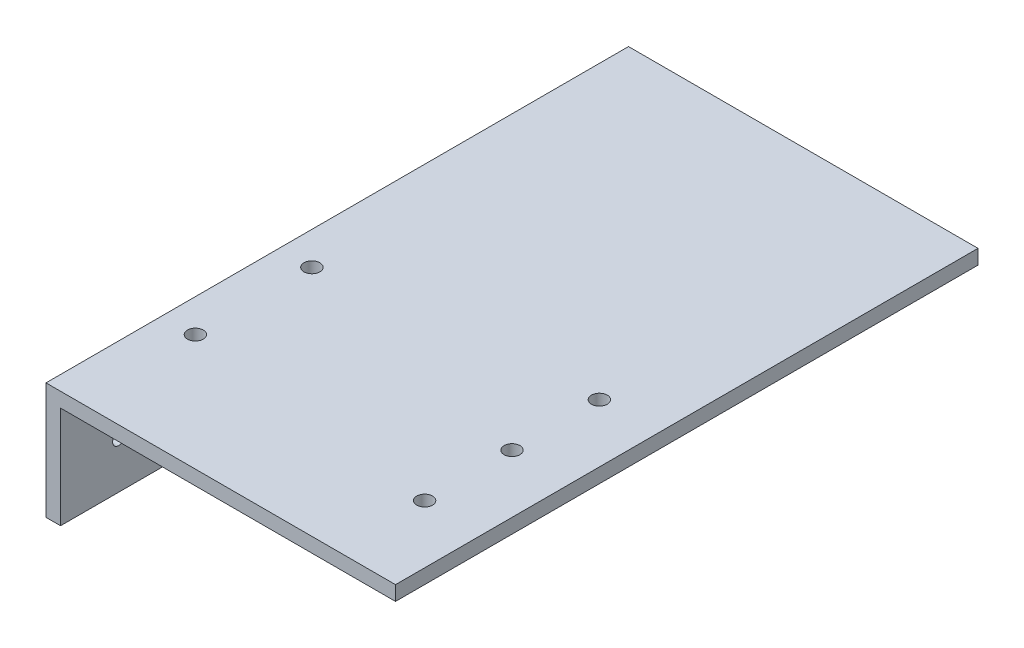
SolidWorks part; units mm, degrees
ref_plane "Front Plane" through (0, 0, 0) normal (0, 0, 1) x (1, 0, 0)
ref_plane "Top Plane" through (0, 0, 0) normal (0, 1, 0) x (1, 0, 0)
ref_plane "Right Plane" through (0, 0, 0) normal (1, 0, 0) x (0, 0, -1)
sketch "Sketch2" plane through (0, 0, 0) normal (0, 0, 1) x (1, 0, 0)
  line L0 (0, 0) -> (-76.2, 0)
  line L1 (-76.2, 0) -> (-76.2, -25.4)
  line L2 (-76.2, -25.4) -> (-73.025, -25.4)
  line L3 (-73.025, -25.4) -> (-73.025, -3.175)
  line L4 (-73.025, -3.175) -> (0, -3.175)
  line L5 (0, -3.175) -> (0, 0)
  dimension "D1" = 76.2
  dimension "D2" = 25.4
  dimension "D3" = 3.175
  dimension "D4" = 3.175
extrude "Boss-Extrude1" add sketch "Sketch2" along normal blind 76.2
sketch "Sketch7" plane through (-76.2, 0, 0) normal (-1, 0, 0) x (0, 0, 1)
  line L1 (0, 0) -> (0, -25.4) construction
  line L2 (0, -15.24) -> (38.1, -15.24) construction
  line L7 (36.449, -16.9885) -> (39.751, -13.4915) construction
  line L8 (36.449, -13.4915) -> (39.751, -16.9885) construction
  circle A0 centre (38.1, -15.24) radius 3.175
  dimension "D1" = 38.1
  dimension "D2" = 3.302
extrude "Cut-Extrude1" cut sketch "Sketch7" against normal up to next
hole_wizard "Tap Drill for #8-32 Tap2" positions "Sketch10" profile "Sketch9" hole size "#8-32" standard "ANSI Inch" end condition through all
sketch "Sketch10" plane through (0, 0, 0) normal (0, 1, 0) x (1, 0, 0)
  line L0 (0, 0) -> (-76.2, 0) construction
  line L1 (0, -76.2) -> (0, 0) construction
  point P0 (-12.7, -19.05)
  point P2 (-12.7, -38.1)
  point P4 (-12.7, -57.15)
  dimension "D1" = 19.05
  dimension "D2" = 19.05
  dimension "D3" = 19.05
  dimension "D4" = 12.7
sketch "Sketch9" plane through (-12.7, 0, 19.05) normal (1, 0, 0) x (0, 0, 1)
  line L0 (0, 0) -> (0, 25.4)
  line L1 (0, 25.4) -> (1.7272, 25.4)
  line L2 (1.7272, 25.4) -> (1.7272, 0)
  line L5 (1.7272, 0) -> (0, 0)
  line L11 (0, -6.35) -> (0, 107.95) construction
  dimension "Thru Hole Dia." = 3.4544
  dimension "Thru Hole Depth" = 25.4
hole_wizard "Tap Drill for #8-32 Tap4" positions "Sketch15" profile "Sketch14" hole size "#8-32" standard "ANSI Inch" end condition up to next
sketch "Sketch15" plane through (0, 0, 0) normal (0, 1, 0) x (1, 0, 0)
  line L0 (0, 0) -> (-76.2, 0) construction
  point P0 (-69.0285, -25.4)
  point P2 (-69.0285, -50.8)
  dimension "D1" = 25.4
  dimension "D2" = 25.4
sketch "Sketch14" plane through (-69.0285, 0, 25.4) normal (1, 0, 0) x (0, 0, 1)
  line L0 (0, 0) -> (0, 3.175)
  line L1 (0, 3.175) -> (1.7272, 3.175)
  line L2 (1.7272, 3.175) -> (1.7272, 0)
  line L5 (1.7272, 0) -> (0, 0)
  line L11 (0, -6.35) -> (0, 107.95) construction
  dimension "Thru Hole Dia." = 3.4544
  dimension "Thru Hole Depth" = 3.175
hole_wizard "Tap Drill for #6-32 Tap1" positions "Sketch17" profile "Sketch16" hole size "#6-32" standard "ANSI Inch" end condition up to next
sketch "Sketch17" plane through (-76.2, 0, 0) normal (-1, 0, 0) x (0, 0, 1)
  line L0 (76.2, 0) -> (0, 0) construction
  line L1 (76.2, 0) -> (76.2, -25.4) construction
  point P0 (50.8, -15.24)
  point P2 (63.5, -15.24)
  dimension "D1" = 12.7
  dimension "D2" = 15.24
  dimension "D3" = 12.7
sketch "Sketch16" plane through (-76.2, -15.24, 50.8) normal (0, 1, 0) x (0, 0, 1)
  line L0 (0, 0) -> (0, 3.175)
  line L1 (0, 3.175) -> (1.3525, 3.175)
  line L2 (1.3525, 3.175) -> (1.3525, 0)
  line L5 (1.3525, 0) -> (0, 0)
  line L11 (0, -6.35) -> (0, 107.95) construction
  dimension "Thru Hole Dia." = 2.7051
  dimension "Thru Hole Depth" = 3.175
sketch "Sketch19" plane through (0, 0, 0) normal (0, 0, -1) x (-1, 0, 0)
  line L0 (0, -3.175) -> (73.025, -3.175)
  line L1 (73.025, -3.175) -> (73.025, -25.4)
  line L2 (73.025, -25.4) -> (76.2, -25.4)
  line L3 (76.2, -25.4) -> (76.2, 0)
  line L4 (76.2, 0) -> (0, 0)
  line L5 (0, 0) -> (0, -3.175)
extrude "Boss-Extrude2" add sketch "Sketch19" along normal blind 50.8
